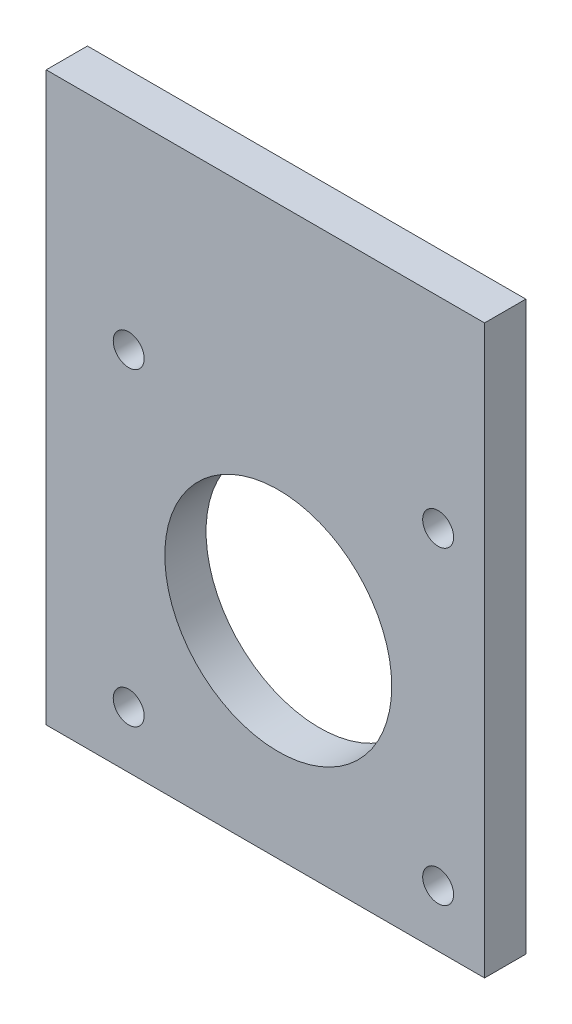
SolidWorks part; units mm, degrees
ref_plane "Front Plane" through (0, 0, 0) normal (0, 0, 1) x (1, 0, 0)
ref_plane "Top Plane" through (0, 0, 0) normal (0, 1, 0) x (1, 0, 0)
ref_plane "Right Plane" through (0, 0, 0) normal (1, 0, 0) x (0, 0, -1)
sketch "Sketch1" plane through (0, 0, 0) normal (0, 0, 1) x (1, 0, 0)
  line L1 (-21.25, 20) -> (21.25, 20)
  line L2 (-21.25, 20) -> (-21.25, -20)
  line L3 (-21.25, -20) -> (21.25, -20)
  line L4 (21.25, 20) -> (21.25, -20)
  line L5 (-21.25, 20) -> (21.25, -20) construction
  line L6 (-21.25, -20) -> (21.25, 20) construction
  point P0 (0, 0)
  dimension "D1" = 42.5
  dimension "D2" = 40
extrude "Boss-Extrude1" add sketch "Sketch1" along normal mid plane 4
sketch "Sketch2" plane through (0, 0, -2) normal (0, 0, -1) x (-1, 0, 0)
  circle A0 centre (-16.75, 15.5) radius 1.5
  circle A1 centre (13.25, 15.5) radius 1.5
  circle A2 centre (13.25, -14.5) radius 1.5
  circle A3 centre (-16.75, -14.5) radius 1.5
  circle A4 centre (-16.75, 15.5) radius 1.5 construction
  dimension "D1" = 0
extrude "Cut-Extrude1" cut sketch "Sketch2" against normal blind 4
sketch "Sketch3" plane through (0, 0, 2) normal (0, 0, 1) x (1, 0, 0)
  circle A7 centre (1.25, 0) radius 11
  circle A8 centre (1.25, 0) radius 11 construction
  dimension "D2" = 0
  dimension "D1" = 0
extrude "Cut-Extrude2" cut sketch "Sketch3" against normal blind 4
sketch "Sketch4" plane through (0, 20, 0) normal (0, 1, 0) x (1, 0, 0)
  line L1 (-21.25, 2) -> (21.25, 2)
  line L2 (-21.25, 2) -> (-21.25, -2)
  line L3 (-21.25, -2) -> (21.25, -2)
  line L4 (21.25, 2) -> (21.25, -2)
extrude "Boss-Extrude2" add sketch "Sketch4" along normal blind 15
